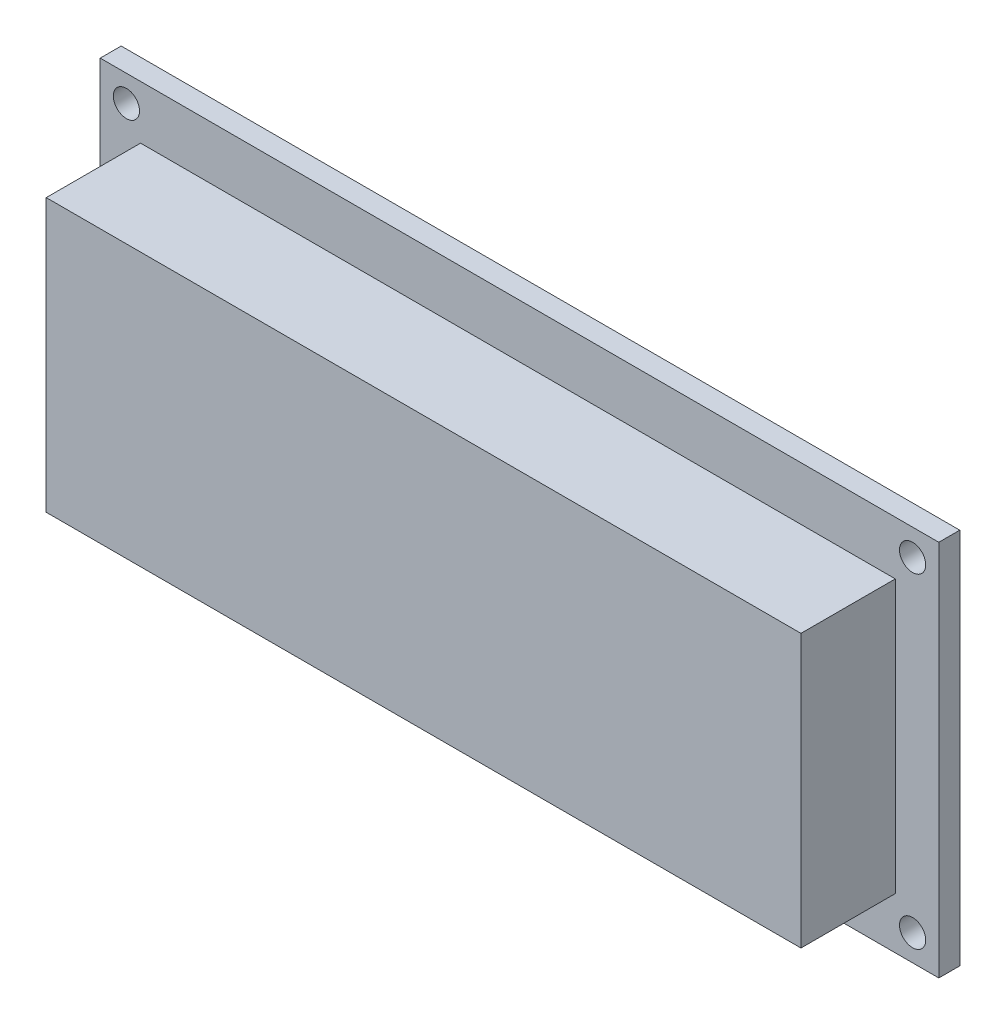
SolidWorks part; units mm, degrees
ref_plane "Спереди" through (0, 0, 0) normal (0, 0, 1) x (1, 0, 0)
ref_plane "Сверху" through (0, 0, 0) normal (0, 1, 0) x (1, 0, 0)
ref_plane "Справа" through (0, 0, 0) normal (1, 0, 0) x (0, 0, -1)
sketch "Эскиз1" plane through (0, 0, 0) normal (0, 0, 1) x (1, 0, 0)
  line L1 (-18.7452, 13.6248) -> (61.2548, 13.6248)
  line L2 (-18.7452, 13.6248) -> (-18.7452, -22.3752)
  line L3 (-18.7452, -22.3752) -> (61.2548, -22.3752)
  line L4 (61.2548, 13.6248) -> (61.2548, -22.3752)
  dimension "D1" = 80
  dimension "D2" = 36
extrude "Бобышка-Вытянуть1" add sketch "Эскиз1" along normal blind 2
sketch "Эскиз2" plane through (0, 0, 2) normal (0, 0, 1) x (1, 0, 0)
  line L0 (61.2548, 13.6248) -> (-18.7452, 13.6248) construction
  line L1 (-14.8952, 8.5248) -> (57.1048, 8.5248)
  line L2 (-14.8952, 8.5248) -> (-14.8952, -17.4752)
  line L3 (-14.8952, -17.4752) -> (57.1048, -17.4752)
  line L4 (57.1048, 8.5248) -> (57.1048, -17.4752)
  line L8 (61.2548, -22.3752) -> (61.2548, 13.6248) construction
  dimension "D1" = 72
  dimension "D2" = 26
  dimension "D3" = 5.1
  dimension "D4" = 4.15
extrude "Бобышка-Вытянуть2" add sketch "Эскиз2" along normal blind 9
sketch "Эскиз3" plane through (0, 0, 2) normal (0, 0, 1) x (1, 0, 0)
  line L0 (61.2548, -22.3752) -> (61.2548, 13.6248) construction
  line L1 (-18.7452, -22.3752) -> (61.2548, -22.3752) construction
  line L2 (61.2548, 13.6248) -> (-18.7452, 13.6248) construction
  line L3 (-18.7452, 13.6248) -> (-18.7452, -22.3752) construction
  circle A0 centre (-16.2452, 11.1248) radius 1.25
  circle A1 centre (58.7548, 11.1248) radius 1.25
  circle A2 centre (58.7548, -19.8752) radius 1.25
  circle A3 centre (-16.2452, -19.8752) radius 1.25
  dimension "D1" = 2.5
  dimension "D2" = 2.5
  dimension "D4" = 2.5
  dimension "D5" = 2.5
  dimension "D6" = 2.5
  dimension "D7" = 2.5
  dimension "D8" = 2.5
  dimension "D9" = 2.5
  dimension "D10" = 2.5
  dimension "D11" = 2.5
  dimension "D12" = 2.5
  dimension "D3" = 2.5
  dimension "D13" = 31
  dimension "D14" = 75
extrude "Вырез-Вытянуть1" cut sketch "Эскиз3" against normal through all
equation "\"1б5\"=2.10104"
